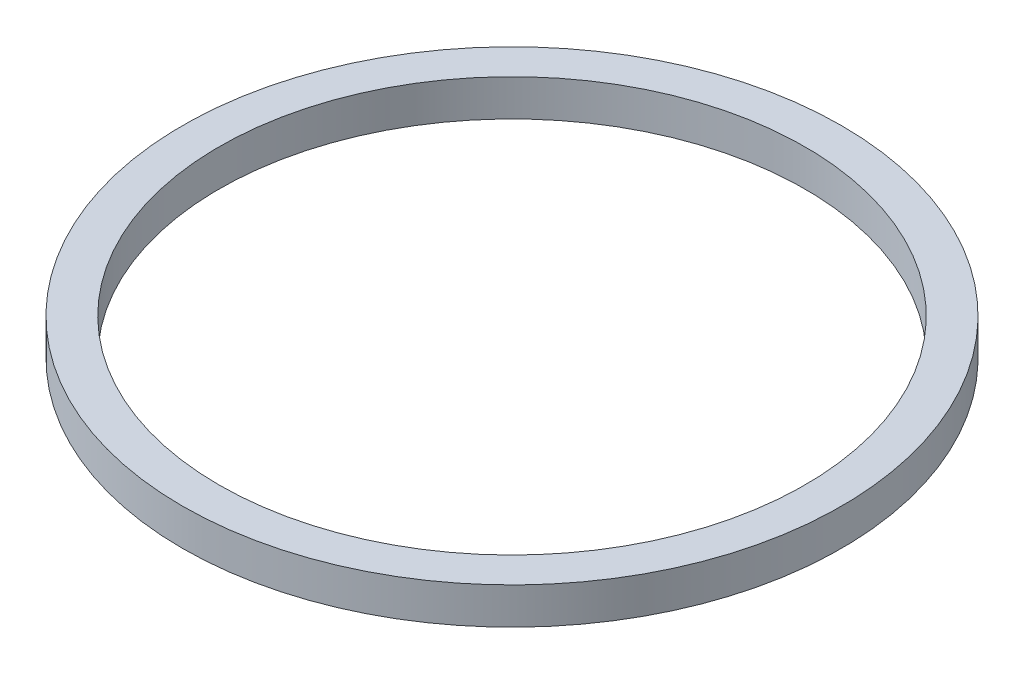
SolidWorks part; units mm, degrees
material "橡胶"
ref_plane "前视基准面" through (0, 0, 0) normal (0, 0, 1) x (1, 0, 0)
ref_plane "上视基准面" through (0, 0, 0) normal (0, 1, 0) x (1, 0, 0)
ref_plane "右视基准面" through (0, 0, 0) normal (1, 0, 0) x (0, 0, -1)
sketch "草图1" plane through (0, 0, 0) normal (0, 1, 0) x (1, 0, 0)
  circle A0 centre (0, 0) radius 0.9
  circle A1 centre (0, 0) radius 0.8
  dimension "D1" = 1.8
  dimension "D2" = 1.6
extrude "凸台-拉伸1" add sketch "草图1" along normal blind 0.1
